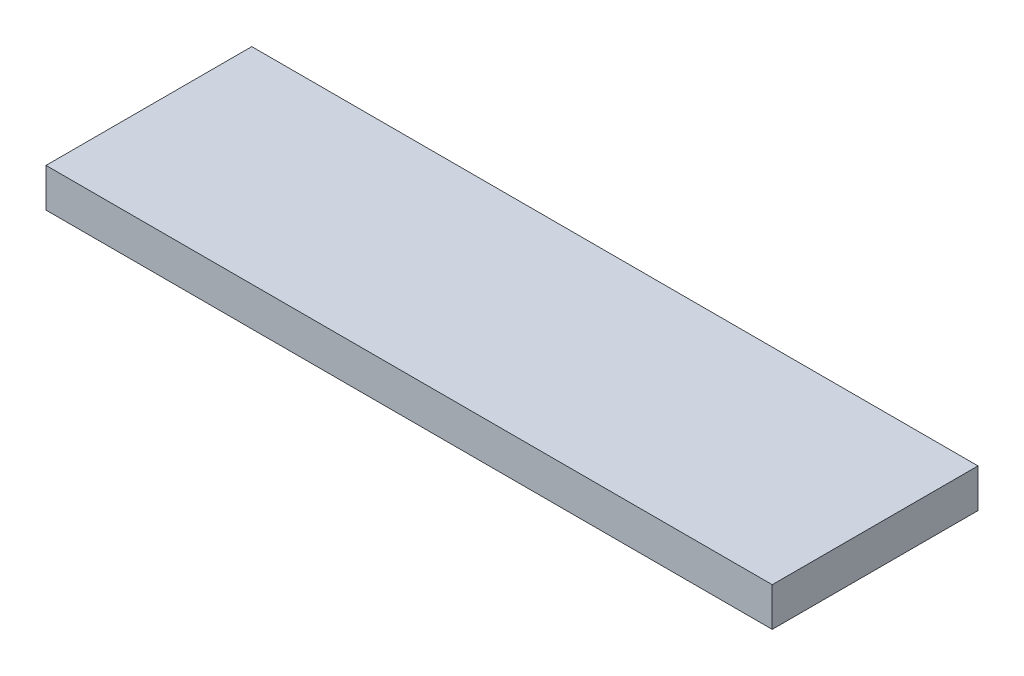
SolidWorks part; units mm, degrees
ref_plane "Front Plane" through (0, 0, 0) normal (0, 0, 1) x (1, 0, 0)
ref_plane "Top Plane" through (0, 0, 0) normal (0, 1, 0) x (1, 0, 0)
ref_plane "Right Plane" through (0, 0, 0) normal (1, 0, 0) x (0, 0, -1)
sketch "Sketch1" plane through (0, 0, 0) normal (0, 1, 0) x (1, 0, 0)
  line L1 (0, 0) -> (30, 0)
  line L2 (0, 0) -> (0, 8.5)
  line L3 (0, 8.5) -> (30, 8.5)
  line L4 (30, 0) -> (30, 8.5)
  dimension "D1" = 8.5
  dimension "D2" = 30
extrude "Boss-Extrude1" add sketch "Sketch1" along normal blind 1.6
equation "\"leftedgewidth\" = 8.5mm"
equation "\"rightedgewidth\" = 10.75mm"
equation "\"innerclipwidth\" = 11.5mm"
equation "\"innerframewidth\" = 99.18mm"
equation "\"framelength\" = 118.4mm"
equation "\"frameextralength\" = 39mm"
equation "\"clipwidth\" = 3mm"
equation "\"cliplength\" = 6mm"
equation "\"clipheight\" = 8mm"
equation "\"basethickness\" = 5mm"
equation "\"framethickness\" = 1.6mm"
equation "\"batterylength\" = 145mm"
equation "\"batterywidth\" = 51mm"
equation "\"D1@Sketch1\"=\"leftedgewidth\""
